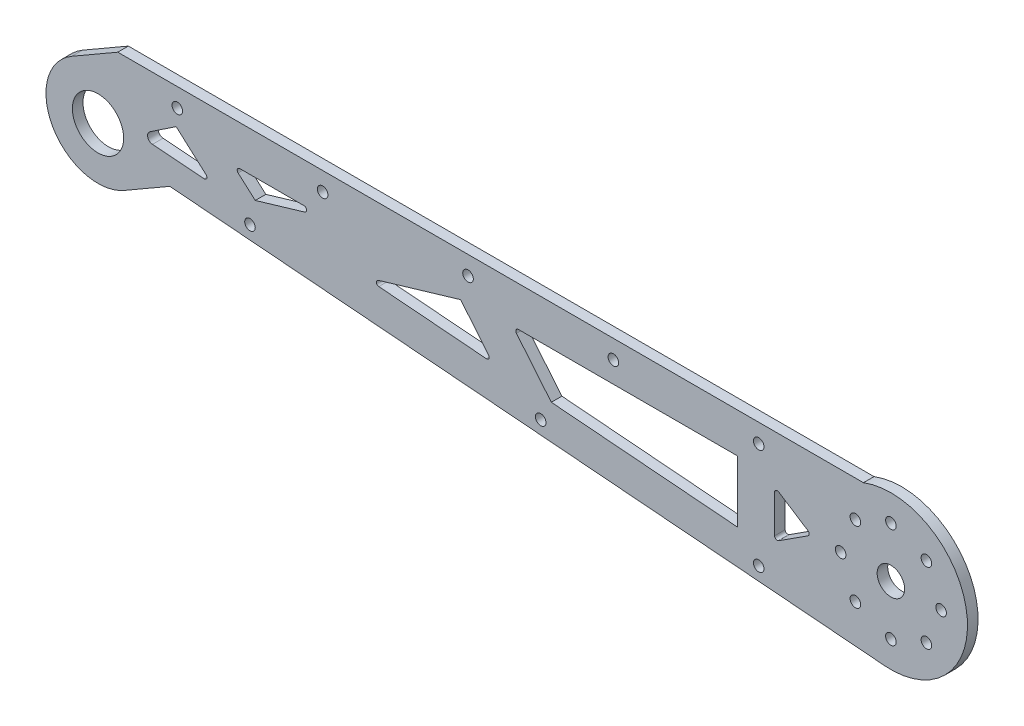
SolidWorks part; units mm, degrees
ref_plane "前视基准面" through (0, 0, 0) normal (0, 0, 1) x (1, 0, 0)
ref_plane "上视基准面" through (0, 0, 0) normal (0, 1, 0) x (1, 0, 0)
ref_plane "右视基准面" through (0, 0, 0) normal (1, 0, 0) x (0, 0, -1)
sketch "草图1" plane through (0, 0, 0) normal (0, 0, 1) x (1, 0, 0)
  line L0 (0, 0) -> (300, 0) construction
  line L1 (0, 0) -> (-15.3092, 26.5163) construction
  line L6 (-9.85, 17.0607) -> (7.4705, 27.0607)
  line L7 (9.85, -17.0607) -> (27.1705, -7.0607)
  line L8 (300, 0) -> (350.6731, 87.7683) construction
  line L9 (27.1705, -7.0607) -> (297.6656, -28.9059)
  line L10 (250, -20) -> (24.502, -1.7888) construction
  line L11 (289.6247, 27.0607) -> (7.4705, 27.0607)
  line L12 (250, 0) -> (250, 20) construction
  line L13 (167.5, -13.3373) -> (195, 20) construction
  line L14 (167.5, -13.3373) -> (140, 20) construction
  line L15 (85, 20) -> (57.5, -4.4537) construction
  line L16 (57.5, -4.4537) -> (30, 20) construction
  circle A0 centre (0, 0) radius 9.7
  circle A1 centre (300, 0) radius 19 construction
  circle A2 centre (300, 0) radius 5.2
  circle A3 centre (319, 0) radius 2
  circle A18 centre (313.435, -13.435) radius 2
  circle A19 centre (300, -19) radius 2
  circle A20 centre (286.565, -13.435) radius 2
  circle A21 centre (281, 0) radius 2
  circle A22 centre (286.565, 13.435) radius 2
  circle A23 centre (300, 19) radius 2
  circle A24 centre (313.435, 13.435) radius 2
  circle A25 centre (0, 0) radius 19.7 construction
  arc A26 (9.85, -17.0607) -> (-9.85, 17.0607) centre (0, 0) cw
  circle A27 centre (300, 0) radius 29 construction
  arc A28 (289.6247, 27.0607) -> (297.6656, -28.9059) centre (299.9992, -0.0097) cw
  circle A29 centre (250, 20) radius 2
  circle A30 centre (195, 20) radius 2
  circle A31 centre (140, 20) radius 2
  circle A32 centre (85, 20) radius 2
  circle A33 centre (30, 20) radius 2
  circle A35 centre (250, -20) radius 2
  circle A37 centre (167.5, -13.3373) radius 2
  circle A38 centre (57.5, -4.4537) radius 2
  dimension "D1" = 19.4
  dimension "D3" = 38
  dimension "D4" = 10.4
  dimension "D5" = 4
  dimension "D6" = 8
  dimension "D7" = 10
  dimension "D10" = 10
  dimension "D13" = 4
  dimension "D2" = 300
  dimension "D8" = 120
  dimension "D9" = 20
  dimension "D11" = 120
  dimension "D12" = 50
  dimension "D14" = 5
extrude "凸台-拉伸1" add sketch "草图1" along normal blind 4
sketch "草图2" plane through (0, 0, 0) normal (0, 0, -1) x (-1, 0, 0)
  line L3 (-137.1976, 10.8253) -> (-106.0437, 1.591)
  line L4 (-106.2474, -0.3645) -> (-146.9399, -3.6508)
  line L5 (-147.7919, -2.0177) -> (-137.1976, 10.8253)
  line L9 (-242, 12) -> (-159.0911, 12)
  line L10 (-77.9672, 12) -> (-53.6651, 12)
  line L11 (-53.0006, 10.2527) -> (-59.4917, 4.4807)
  line L12 (-171.5176, -5.6357) -> (-158.3196, 10.3637)
  line L13 (-242, -11.3279) -> (-171.5176, -5.6357)
  line L14 (-242, 12) -> (-242, -11.3279)
  line L18 (-59.4917, 4.4807) -> (-78.2514, 10.0412)
  line L22 (-268.63, 0.8403) -> (-257.5421, 7.9938)
  line L23 (-256, 7.1535) -> (-256, -7.1535)
  line L24 (-257.5421, -7.9938) -> (-268.63, -0.8403)
  line L32 (-19.6317, 7.0786) -> (-29.5619, 13.6987)
  line L33 (-29.5619, 13.6987) -> (-40.8603, 3.6519)
  line L34 (-40.1186, 1.9076) -> (-20.5867, 3.4204)
  arc A2 (-20.5867, 3.4204) -> (-19.6317, 7.0786) centre (-20.7411, 5.4145) ccw
  arc A3 (-40.1186, 1.9076) -> (-40.8603, 3.6519) centre (-40.1958, 2.9046) cw
  arc A4 (-158.3196, 10.3637) -> (-159.0911, 12) centre (-159.0911, 11) ccw
  arc A5 (-53.0006, 10.2527) -> (-53.6651, 12) centre (-53.6651, 11) ccw
  arc A6 (-78.2514, 10.0412) -> (-77.9672, 12) centre (-77.9672, 11) cw
  arc A7 (-106.2474, -0.3645) -> (-106.0437, 1.591) centre (-106.3279, 0.6323) ccw
  arc A8 (-146.9399, -3.6508) -> (-147.7919, -2.0177) centre (-147.0204, -2.6541) cw
  arc A9 (-256, 7.1535) -> (-257.5421, 7.9938) centre (-257, 7.1535) ccw
  arc A10 (-256, -7.1535) -> (-257.5421, -7.9938) centre (-257, -7.1535) cw
  arc A11 (-268.63, -0.8403) -> (-268.63, 0.8403) centre (-268.0879, 0) cw
  dimension "D1" = 2
  dimension "D3" = 1
  dimension "D2" = 1
extrude "切除-拉伸1" cut sketch "草图2" against normal blind 10
